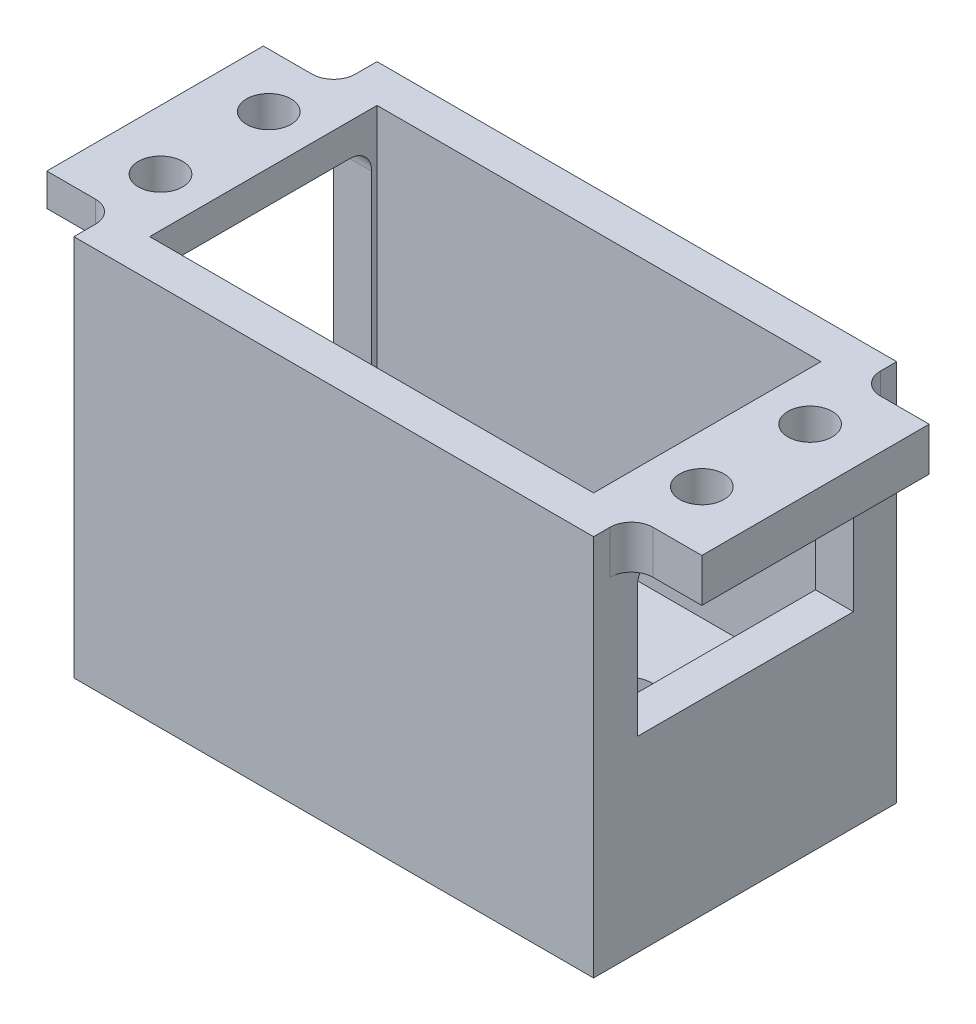
SolidWorks part; units mm, degrees
ref_plane "前视基准面" through (0, 0, 0) normal (0, 0, 1) x (1, 0, 0)
ref_plane "上视基准面" through (0, 0, 0) normal (0, 1, 0) x (1, 0, 0)
ref_plane "右视基准面" through (0, 0, 0) normal (1, 0, 0) x (0, 0, -1)
other "Configuration Table"
sketch "草图1" plane through (0, 0, 0) normal (0, 1, 0) x (1, 0, 0)
  line L0 (-24, 14) -> (24, 14)
  line L1 (-20, -10) -> (20, -10) construction
  line L2 (-20, -10) -> (-20, 10) construction
  line L3 (-20, 10) -> (20, 10) construction
  line L4 (20, -10) -> (20, 10) construction
  line L5 (-20, -10) -> (20, 10) construction
  line L6 (-20, 10) -> (20, -10) construction
  line L7 (24, -14) -> (24, 14)
  line L8 (-24, -14) -> (24, -14)
  line L9 (-24, -14) -> (-24, 14)
  point P0 (0, 0)
  dimension "D1" = 40
  dimension "D2" = 20
  dimension "D3" = 4
extrude "凸台-拉伸1" add sketch "草图1" along normal blind 9.3
sketch "草图2" plane through (0, 9.3, 0) normal (0, 1, 0) x (1, 0, 0)
  line L0 (-24, 14) -> (24, 14)
  line L1 (-20, -10) -> (20, -10)
  line L2 (-20, -10) -> (-20, 10)
  line L3 (-20, 10) -> (20, 10)
  line L4 (20, -10) -> (20, 10)
  line L5 (-20, -10) -> (20, 10) construction
  line L6 (-20, 10) -> (20, -10) construction
  line L7 (24, -14) -> (24, 14)
  line L8 (-24, -14) -> (24, -14)
  line L9 (-24, -14) -> (-24, 14)
  point P0 (0, 0)
  dimension "D1" = 40
  dimension "D2" = 20
  dimension "D3" = 4
extrude "凸台-拉伸2" add sketch "草图2" along normal blind 26
sketch "草图3" plane through (0, 35.3, 0) normal (0, 1, 0) x (1, 0, 0)
  line L1 (-20.5, -10.5) -> (20.5, -10.5)
  line L2 (-20.5, -10.5) -> (-20.5, 10.5)
  line L3 (-20.5, 10.5) -> (20.5, 10.5)
  line L4 (20.5, -10.5) -> (20.5, 10.5)
  line L5 (-20.5, -10.5) -> (20.5, 10.5) construction
  line L6 (-20.5, 10.5) -> (20.5, -10.5) construction
  point P0 (0, 0)
  dimension "D1" = 21
  dimension "D2" = 41
extrude "切除-拉伸1" cut sketch "草图3" against normal blind 26
sketch "草图4" plane through (24, 0, 0) normal (1, 0, 0) x (0, 0, -1)
  line L0 (-9.9569, 35.3) -> (-9.9569, 17.3)
  line L1 (-14, 35.3) -> (14, 35.3) construction
  line L2 (-9.9569, 17.3) -> (10, 17.3)
  line L3 (10, 17.3) -> (10, 35.3)
  line L4 (10, 0) -> (10, 47) construction
  line L5 (-9.9569, 35.3) -> (10, 35.3)
  dimension "D1" = 18
extrude "切除-拉伸2" cut sketch "草图4" against normal blind 10
sketch "草图6" plane through (-24, 0, 0) normal (-1, 0, 0) x (0, 0, 1)
  line L0 (0, 35.3) -> (-10, 35.3)
  line L1 (-14, 35.3) -> (14, 35.3) construction
  line L2 (-10, 47) -> (-10, 0) construction
  line L3 (-10, 35.3) -> (-10, 10.3)
  line L4 (-10, 10.3) -> (10, 10.3)
  line L5 (10, 10.3) -> (10, 35.3)
  line L6 (10, 35.3) -> (0, 35.3)
  line L7 (10, 44.3) -> (10, 37.8) construction
  dimension "D1" = 25
extrude "切除-拉伸3" cut sketch "草图6" against normal blind 6
sketch "草图7" plane through (-20.5, 0, 0) normal (1, 0, 0) x (0, 0, -1)
  line L0 (10, 35.3) -> (-10, 35.3)
  line L1 (-10, 35.3) -> (-10, 32.3)
  line L2 (-10, 10.3) -> (-10, 35.3) construction
  line L3 (-10, 32.3) -> (10, 32.3)
  line L4 (10, 35.3) -> (10, 10.3) construction
  line L5 (10, 32.3) -> (10, 35.3)
  dimension "D1" = 3
extrude "凸台-拉伸4" add sketch "草图7" against normal blind 10
fillet "圆角3" radius 2 2 edges at (-24, 33.8, 10) (-24, 33.8, -10)
sketch "草图9" plane through (20.5, 0, 0) normal (-1, 0, 0) x (0, 0, 1)
  line L2 (10.5, 35.3) -> (-10.5, 35.3)
  line L3 (-10.5, 35.3) -> (-10.5, 31.3)
  line L4 (-10.5, 31.3) -> (10.5, 31.3)
  line L5 (10.5, 9.3) -> (10.5, 35.3) construction
  line L6 (10.5, 31.3) -> (10.5, 35.3)
  dimension "D1" = 4
extrude "凸台-拉伸5" add sketch "草图9" against normal blind 10
sketch "草图10" plane through (0, 35.3, 0) normal (0, 1, 0) x (1, 0, 0)
  circle A0 centre (25, 5) radius 2.05
  circle A1 centre (25, -5) radius 2.05
  circle A2 centre (-25, 5) radius 2.05
  circle A3 centre (-25, -5) radius 2.05
  dimension "D1" = 4.1
  dimension "D2" = 4.1
  dimension "D3" = 4.1
  dimension "D4" = 4.1
extrude "切除-拉伸5" cut sketch "草图10" against normal blind 10
fillet "圆角4" radius 2 2 edges at (24, 33.3, 10.5) (24, 33.3, -10.5)
sketch "草图11" plane through (0, 9.3, 0) normal (0, 1, 0) x (1, 0, 0)
  line L0 (0, 17.3104) -> (0, -17.5303) construction
  line L1 (-34.178, 0) -> (37.322, 0) construction
  circle A0 centre (-14, 0) radius 3
  circle A1 centre (12.5292, 0) radius 3
  dimension "D1" = 14
  dimension "D2" = 6
  dimension "D3" = 6
extrude "切除-拉伸6" cut sketch "草图11" against normal blind 5.3
sketch "草图12" plane through (0, 4, 0) normal (0, 1, 0) x (1, 0, 0)
  circle A0 centre (-14, 0) radius 2.1
  circle A1 centre (12.5292, 0) radius 2.1
  dimension "D1" = 4.2
  dimension "D2" = 4.2
extrude "切除-拉伸7" cut sketch "草图12" against normal through all both and the other way through all
fillet "圆角5" radius 2 4 edges at (22.25, 31.3, 9.9569) (22.25, 31.3, -10) (-22.25, 32.3, 10) (-22.25, 32.3, -10)
